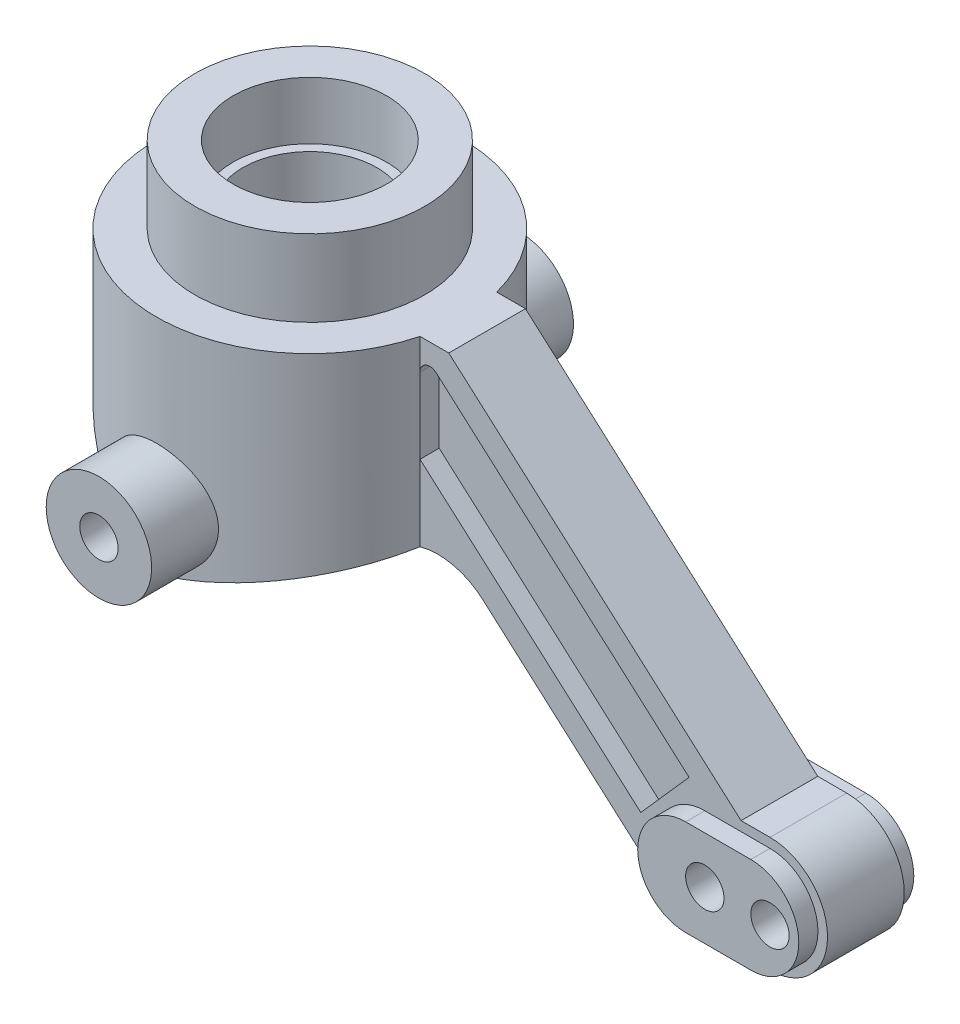
SolidWorks part; units mm, degrees
material "普通碳钢"
ref_plane "前视" through (0, 0, 0) normal (0, 0, 1) x (1, 0, 0)
ref_plane "上视" through (0, 0, 0) normal (0, 1, 0) x (1, 0, 0)
ref_plane "右视" through (0, 0, 0) normal (1, 0, 0) x (0, 0, -1)
sketch "草图1" plane through (0, 0, 0) normal (0, 0, 1) x (1, 0, 0)
  line L0 (0, 0) -> (0, -16.3821) construction
  line L1 (4, 0) -> (4, -3)
  line L2 (4, -3) -> (3.5, -3)
  line L3 (3.5, -3) -> (3.5, -6)
  line L4 (3.5, -6) -> (6, -6)
  line L5 (6, -6) -> (6, -9.5)
  line L6 (6, -9.5) -> (6.25, -9.5)
  line L7 (6.25, -9.5) -> (6.25, -16)
  line L8 (6.25, -16) -> (8, -16)
  line L9 (8, -16) -> (8, -4)
  line L10 (8, -4) -> (6, -4)
  line L11 (6, -4) -> (6, 0)
  line L12 (6, 0) -> (4, 0)
  dimension "D1" = 16
  dimension "D2" = 12
  dimension "D3" = 8
  dimension "D4" = 16
  dimension "D5" = 7
  dimension "D6" = 3
  dimension "D7" = 3
  dimension "D8" = 4
  dimension "D9" = 12
  dimension "D10" = 12.5
  dimension "D11" = 3.5
revolve "旋转1" add sketch "草图1" angle 360 about L0
sketch "草图2" plane through (0, -4, 0) normal (0, 1, 0) x (1, 0, 0)
  line L0 (-8, 0) -> (32, 0) construction
  line L1 (7.746, 2) -> (32, 2)
  line L2 (7.746, -2) -> (32, -2)
  line L3 (32, 2) -> (32, -2)
  circle A0 centre (0, 0) radius 8 construction
  arc A1 (7.746, -2) -> (7.746, 2) centre (0, 0) ccw
  dimension "D1" = 4
  dimension "D2" = 40
extrude "凸台-拉伸1" add sketch "草图2" against normal blind 29
ref_plane "基准面1" through (0, 0, -12) normal (0, 0, -1) x (-1, 0, 0)
sketch "草图3" plane through (0, 0, -12) normal (0, 0, -1) x (-1, 0, 0)
  line L0 (8, -10) -> (1.8605, -14.8534)
  line L1 (-0.7882, -15.3946) -> (-7.746, -13.5)
  line L2 (-7.746, -16) -> (-7.746, -4) construction
  line L3 (-11.0379, -14.2689) -> (-20.6112, -22.746)
  line L4 (-22.6, -23.5) -> (-26, -23.5)
  line L5 (-26, -17.5) -> (-24.4916, -17.5)
  line L6 (-24.4916, -17.5) -> (-9.246, -4)
  line L7 (-32, -4) -> (-7.746, -4) construction
  line L8 (6, 0) -> (-6, 0) construction
  line L9 (8, -16) -> (8, -4) construction
  line L10 (-29, -20.5) -> (-19.6, -20.5) construction
  line L11 (-22.6, -20.5) -> (-26, -20.5) construction
  line L12 (-24.3, -20.5) -> (-24.3, -23.5) construction
  line L13 (8, -4) -> (-7.746, -4) construction
  line L14 (0, 0) -> (0, -16) construction
  line L15 (-7.746, -16) -> (8, -16) construction
  line L16 (8, -16) -> (8, -4) construction
  line L17 (8, -10) -> (8, -16)
  line L18 (8, -16) -> (-7.746, -16)
  line L19 (-7.746, -16) -> (-7.746, -33)
  line L20 (-7.746, -33) -> (-32, -33)
  line L21 (-32, -33) -> (-7.746, -33) construction
  line L22 (-32, -33) -> (-32, -4)
  line L23 (-32, -33) -> (-32, -4) construction
  line L24 (-32, -4) -> (-9.246, -4)
  arc A0 (1.8605, -14.8534) -> (-0.7882, -15.3946) centre (0, -12.5) cw
  arc A1 (-22.6, -23.5) -> (-20.6112, -22.746) centre (-22.6, -20.5) ccw
  arc A2 (-26, -23.5) -> (-26, -17.5) centre (-26, -20.5) cw
  arc A3 (-7.746, -13.5) -> (-11.0379, -14.2689) centre (-8.6803, -16.9313) ccw
  circle A4 centre (0, -12.5) radius 3 construction
  circle A5 centre (-27, -20.5) radius 1 construction
  circle A6 centre (-23.6, -20.5) radius 1 construction
  point P24 (-24.3, -20.5)
  dimension "D4" = 37
  dimension "D9" = 9.5
  dimension "D10" = 6
  dimension "D11" = 2
  dimension "D12" = 3.4
  dimension "D13" = 8
  dimension "D14" = 27
  dimension "D1" = 1.5
  dimension "D2" = 10
  dimension "D3" = 15.5
  dimension "D5" = 6
  dimension "D6" = 6.5
  dimension "D8" = 9.4
extrude "切除-拉伸1" cut sketch "草图3" against normal blind 29
sketch "草图4" plane through (0, 0, -2) normal (0, 0, -1) x (-1, 0, 0)
  line L0 (-15.8245, -18.5074) -> (-20.1337, -13.6411) construction
  line L1 (-11.0379, -14.2689) -> (-20.6112, -22.746) construction
  line L2 (-24.4916, -17.5) -> (-9.246, -4) construction
  line L3 (-29, -20.5) -> (-19.6, -20.5) construction
  line L4 (-24.3, -20.5) -> (-24.3, -18) construction
  line L5 (-20.1, -20.5) -> (-28.5, -20.5) construction
  line L6 (-22.6, -23) -> (-26, -23) construction
  line L7 (-22.6, -18) -> (-26, -18) construction
  line L8 (-19.2601, -19.7465) -> (-21.7793, -16.9015)
  line L9 (-21.7793, -16.9015) -> (-8.5954, -5.2272)
  line L10 (-7.746, -13.5) -> (-7.746, -4) construction
  line L11 (-7.746, -5.6096) -> (-7.746, -9.5506)
  line L12 (-7.746, -9.5506) -> (-19.2601, -19.7465)
  line L13 (-17.9791, -16.0743) -> (-7.822, -7.0801) construction
  line L14 (8, -4) -> (-7.746, -4) construction
  arc A0 (-26, -17.5) -> (-26, -23.5) centre (-26, -20.5) ccw construction
  arc A1 (-26, -23) -> (-26, -18) centre (-26, -20.5) cw construction
  arc A2 (-22.6, -23) -> (-22.6, -18) centre (-22.6, -20.5) ccw construction
  arc A3 (-7.746, -5.6096) -> (-8.5954, -5.2272) centre (-8.2568, -5.6096) ccw
  dimension "D3" = 2.5
  dimension "D1" = 9.4
  dimension "D2" = 8.4
  dimension "D4" = 3.8
  dimension "D5" = 0.5
  dimension "D6" = 3.0811
  dimension "D7" = 1.6096
extrude "切除-拉伸2" cut sketch "草图4" against normal blind 1
fillet "圆角1" radius 0.5 2 edges at (21.7793, -16.9015, -1.5) (19.2601, -19.7465, -1.5)
sketch "草图5" plane through (0, 0, -2) normal (0, 0, -1) x (-1, 0, 0)
  line L0 (-29, -20.5) -> (-19.6, -20.5) construction
  line L1 (-28.5, -20.5) -> (-20.1, -20.5) construction
  line L2 (-22.6, -20.5) -> (-26, -20.5) construction
  line L3 (-22.6, -23) -> (-26, -23)
  line L4 (-22.6, -18) -> (-26, -18)
  arc A0 (-26, -17.5) -> (-26, -23.5) centre (-26, -20.5) ccw construction
  arc A1 (-22.6, -23) -> (-22.6, -18) centre (-22.6, -20.5) ccw
  arc A2 (-26, -18) -> (-26, -23) centre (-26, -20.5) ccw
  point P9 (-24.3, -20.5)
  dimension "D1" = 9.4
  dimension "D2" = 8.4
  dimension "D3" = 0.5
  dimension "D4" = 5
extrude "凸台-拉伸2" add sketch "草图5" along normal blind 1
ref_plane "基准面2" through (0, 0, 0) normal (0, 0, -1) x (-1, 0, 0)
mirror "镜向1" about plane through (0, 0, 0) normal (0, 0, -1) of "凸台-拉伸2", "切除-拉伸2"
ref_plane "基准面3" through (0, 0, -11) normal (0, 0, -1) x (-1, 0, 0)
sketch "草图7" plane through (0, 0, -11) normal (0, 0, -1) x (-1, 0, 0)
  line L0 (0, 0) -> (0, -15.5) construction
  line L1 (6, 0) -> (-6, 0) construction
  arc A0 (-0.7882, -15.3946) -> (1.8605, -14.8534) centre (0, -12.5) ccw construction
  circle A1 centre (0, -12.45) radius 2.75
  circle A2 centre (0, -12.45) radius 1
  dimension "D1" = 5.5
  dimension "D2" = 12.45
  dimension "D3" = 2
extrude "凸台-拉伸5" add sketch "草图7" against normal blind 22
sketch "草图8" plane through (0, -9.5, 0) normal (0, -1, 0) x (1, 0, 0)
  circle A0 centre (0, 0) radius 6.25
extrude "切除-拉伸4" cut sketch "草图8" along normal blind 19
sketch "草图9" plane through (0, 0, -3) normal (0, 0, -1) x (-1, 0, 0)
  line L0 (-23.6, -20.45) -> (-27, -20.45) construction
  circle A0 centre (-27, -20.45) radius 1
  circle A1 centre (-23.6, -20.45) radius 1
  circle A2 centre (0, -12.45) radius 1 construction
  circle A5 centre (0, -12.45) radius 2.75 construction
  dimension "D1" = 2
  dimension "D3" = 8
  dimension "D4" = 27
  dimension "D2" = 3.4
extrude "切除-拉伸5" cut sketch "草图9" against normal blind 18
sketch "草图10" plane through (0, 0, -11) normal (0, 0, -1) x (-1, 0, 0)
  circle A0 centre (0, -12.45) radius 1
extrude "切除-拉伸6" cut sketch "草图10" against normal blind 26
